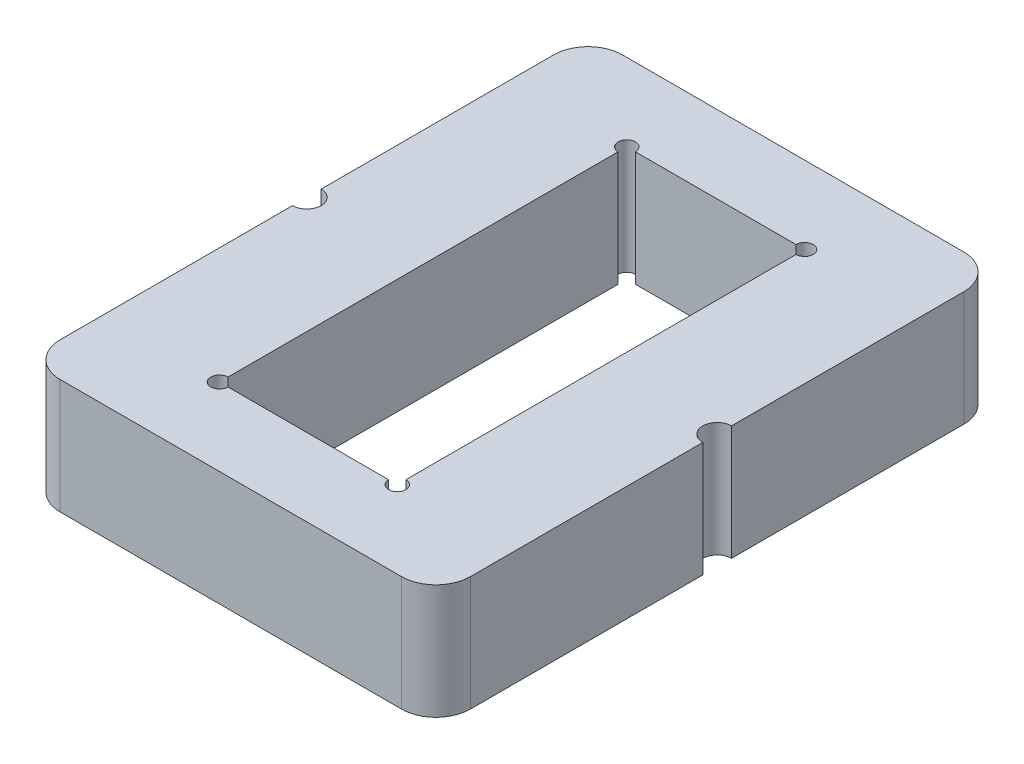
SolidWorks part; units mm, degrees
material "Q235"
ref_plane "前视基准面" through (0, 0, 0) normal (0, 0, 1) x (1, 0, 0)
ref_plane "上视基准面" through (0, 0, 0) normal (0, 1, 0) x (1, 0, 0)
ref_plane "右视基准面" through (0, 0, 0) normal (1, 0, 0) x (0, 0, -1)
sketch "草图1" plane through (0, 0, 0) normal (0, 1, 0) x (1, 0, 0)
  line L0 (0, 98) -> (0, -98) construction
  line L9 (-71.5, -98) -> (71.5, -98)
  line L10 (-71.5, -98) -> (-71.5, 98)
  line L11 (-71.5, 98) -> (71.5, 98)
  line L12 (71.5, -98) -> (71.5, 98)
  line L13 (-71.5, 0) -> (71.5, 0) construction
  line L15 (-31, 71) -> (31, 71)
  line L16 (-31, 71) -> (-31, -71)
  line L17 (-31, -71) -> (31, -71)
  line L18 (31, 71) -> (31, -71)
  line L19 (-31, 71) -> (31, -71) construction
  line L20 (-31, -71) -> (31, 71) construction
  point P11 (0, 0)
  dimension "D1" = 143
  dimension "D2" = 196
  dimension "D3" = 142
  dimension "D4" = 62
extrude "凸台-拉伸1" add sketch "草图1" along normal mid plane 40
fillet "圆角1" radius 12 4 edges at (71.5, 0, -98) (71.5, 0, 98) (-71.5, 0, -98) (-71.5, 0, 98)
sketch "草图2" plane through (0, 20, 0) normal (0, 1, 0) x (1, 0, 0)
  line L0 (-31, -71) -> (31, -71) construction
  line L1 (-31, 71) -> (-31, -71) construction
  circle A0 centre (-31, 71) radius 3
  circle A1 centre (31, 71) radius 3
  circle A2 centre (31, -71) radius 3
  circle A3 centre (-31, -71) radius 3
  dimension "D1" = 6
  dimension "D2" = 6
  dimension "D3" = 6
  dimension "D4" = 6
extrude "切除-拉伸1" cut sketch "草图2" against normal blind 40
sketch "草图3" plane through (0, 20, 0) normal (0, 1, 0) x (1, 0, 0)
  line L3 (-71.5, 86) -> (-71.5, -86) construction
  line L5 (71.5, -86) -> (71.5, 86) construction
  circle A0 centre (-71.5, 0) radius 5
  circle A1 centre (71.5, 0) radius 5
  dimension "D1" = 10
  dimension "D2" = 10
extrude "切除-拉伸2" cut sketch "草图3" against normal blind 40
